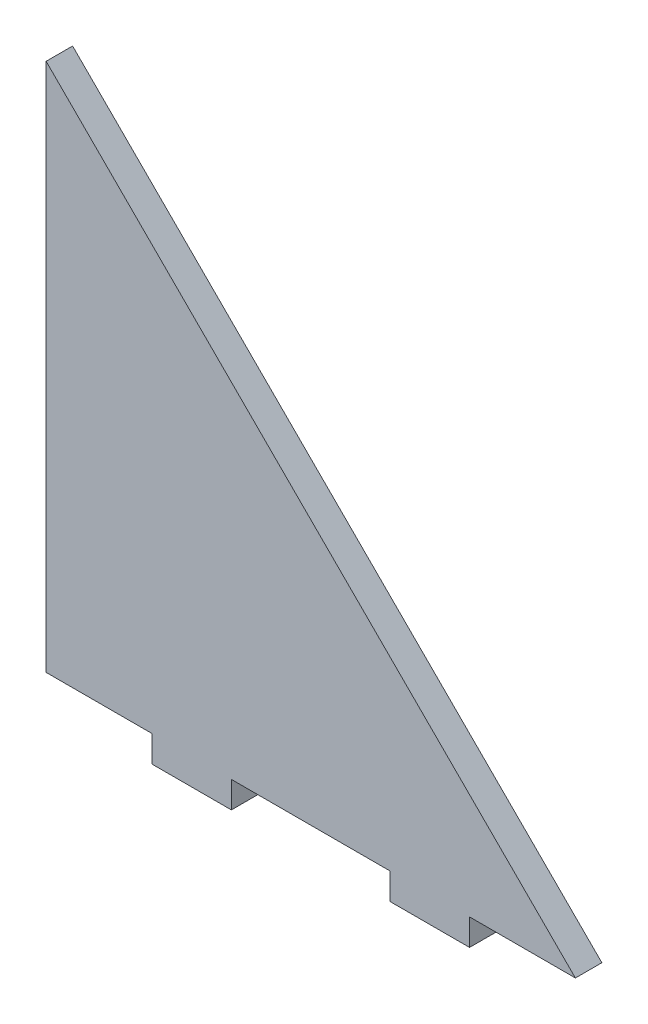
SolidWorks part; units mm, degrees
ref_plane "Front Plane" through (0, 0, 0) normal (0, 0, 1) x (1, 0, 0)
ref_plane "Top Plane" through (0, 0, 0) normal (0, 1, 0) x (1, 0, 0)
ref_plane "Right Plane" through (0, 0, 0) normal (1, 0, 0) x (0, 0, -1)
sketch "Sketch1" plane through (0, 0, 0) normal (0, 0, 1) x (1, 0, 0)
  line L0 (0, 100) -> (0, 0)
  line L1 (0, 0) -> (20, 0)
  line L2 (100, 0) -> (0, 100)
  line L3 (80, 0) -> (100, 0)
  line L5 (20, 0) -> (20, -5)
  line L6 (20, -5) -> (35, -5)
  line L7 (35, 0) -> (35, -5)
  line L8 (35, 0) -> (65, 0)
  line L9 (65, 0) -> (65, -5)
  line L10 (65, -5) -> (80, -5)
  line L11 (80, 0) -> (80, -5)
  dimension "D1" = 45
  dimension "D2" = 100
  dimension "D3" = 15
  dimension "D4" = 5
  dimension "D5" = 20
  dimension "D6" = 30
extrude "Boss-Extrude1" add sketch "Sketch1" along normal blind 5
